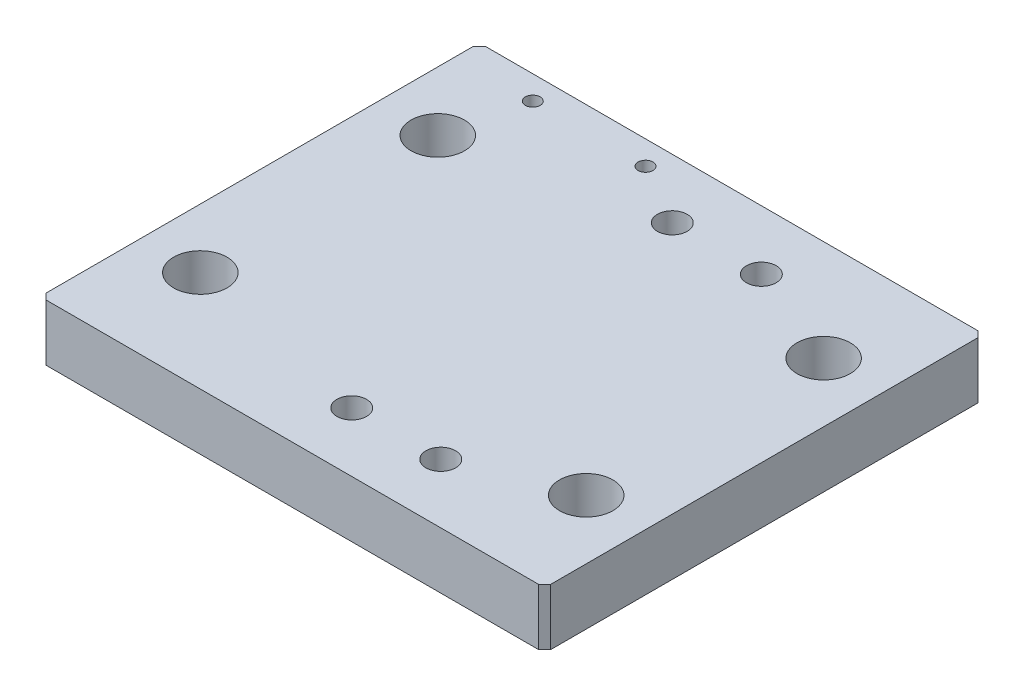
SolidWorks part; units mm, degrees
ref_plane "Front Plane" through (0, 0, 0) normal (0, 0, 1) x (1, 0, 0)
ref_plane "Top Plane" through (0, 0, 0) normal (0, 1, 0) x (1, 0, 0)
ref_plane "Right Plane" through (0, 0, 0) normal (1, 0, 0) x (0, 0, -1)
sketch "Sketch1" plane through (0, 0, 0) normal (0, 1, 0) x (1, 0, 0)
  line L0 (-29.5, 33) -> (-10.5, 33) construction
  line L1 (-42.5, 37) -> (42.5, 37)
  line L2 (-42.5, 37) -> (-42.5, -37)
  line L3 (-42.5, -37) -> (42.5, -37)
  line L4 (42.5, 37) -> (42.5, -37)
  line L5 (-42.5, 37) -> (42.5, -37) construction
  line L6 (-42.5, -37) -> (42.5, 37) construction
  line L7 (32.5, 20) -> (-32.5, 20) construction
  line L8 (32.5, 20) -> (32.5, -20) construction
  line L9 (32.5, -20) -> (-32.5, -20) construction
  line L10 (-32.5, 20) -> (-32.5, -20) construction
  line L11 (32.5, 20) -> (-32.5, -20) construction
  line L12 (32.5, -20) -> (-32.5, 20) construction
  line L13 (0, 27) -> (15, 27) construction
  line L14 (0, 27) -> (0, -27) construction
  line L15 (0, -27) -> (15, -27) construction
  line L16 (15, 27) -> (15, -27) construction
  point P0 (0, 0)
  point P6 (0, 0)
  point P17 (-20, 33)
  dimension "D1" = 15
  dimension "D2" = 54
  dimension "D3" = 65
  dimension "D4" = 40
  dimension "D5" = 10
  dimension "D6" = 10
  dimension "D7" = 19
  dimension "D8" = 20
  dimension "D9" = 33
extrude "Boss-Extrude1" add sketch "Sketch1" along normal blind 9.525
hole_wizard "M8 Clearance Hole1" positions "Sketch2" profile "Sketch3" hole size "M8" standard "ANSI Metric" end condition through all
sketch "Sketch2" plane through (0, 9.525, 0) normal (0, 1, 0) x (1, 0, 0)
  point P0 (-32.5, 20)
  point P3 (32.5, 20)
  point P6 (32.5, -20)
  point P9 (-32.5, -20)
sketch "Sketch3" plane through (-32.5, 9.525, -20) normal (1, 0, 0) x (0, 0, 1)
  line L0 (0, 0) -> (0, 9.525)
  line L1 (0, 9.525) -> (4.5, 9.525)
  line L2 (4.5, 9.525) -> (4.5, 0)
  line L5 (4.5, 0) -> (0, 0)
  line L11 (0, -6.35) -> (0, 107.95) construction
  dimension "Thru Hole Dia." = 9
  dimension "Thru Hole Depth" = 9.525
hole_wizard "M6x1.0 Tapped Hole1" positions "Sketch4" profile "Sketch5" tap size "M6x1.0" standard "ANSI Metric" end condition up to next
sketch "Sketch4" plane through (0, 9.525, 0) normal (0, 1, 0) x (1, 0, 0)
  point P0 (0, 27)
  point P3 (15, 27)
  point P6 (15, -27)
  point P9 (0, -27)
sketch "Sketch5" plane through (0, 9.525, -27) normal (1, 0, 0) x (0, 0, 1)
  line L0 (0, 0) -> (0, 9.525)
  line L1 (0, 9.525) -> (2.5, 9.525)
  line L2 (2.5, 9.525) -> (2.5, 0)
  line L5 (2.5, 0) -> (0, 0)
  line L11 (0, -6.35) -> (0, 107.95) construction
  dimension "Thru Tap Drill Dia." = 5
  dimension "Thru Tap Drill Depth" = 9.525
cosmetic thread "Hole Thread1" parameters "D2"=6
cosmetic thread "Hole Thread2" parameters "D2"=6
cosmetic thread "Hole Thread3" parameters "D2"=6
cosmetic thread "Hole Thread4" parameters "D2"=6
hole_wizard "M6x1.0 Tapped Hole2" [suppressed] positions "Sketch8" profile "Sketch9" tap size "M6x1.0" standard "ANSI Metric"
sketch "Sketch8" plane through (0, 9.525, 0) normal (0, 1, 0) x (1, 0, 0)
  point P0 (0, 27)
  point P3 (0, -27)
sketch "Sketch9" plane through (0, 9.525, -27) normal (1, 0, 0) x (0, 0, 1)
  line L0 (0, 0) -> (0, 9.525)
  line L1 (0, 9.525) -> (2.5, 9.525)
  line L2 (2.5, 9.525) -> (2.5, 0)
  line L5 (2.5, 0) -> (0, 0)
  line L11 (0, -6.35) -> (0, 107.95) construction
  dimension "Thru Tap Drill Dia." = 5
  dimension "Thru Tap Drill Depth" = 9.525
cosmetic thread "Hole Thread7" [suppressed] parameters "D2"=6
cosmetic thread "Hole Thread8" [suppressed] parameters "D2"=6
hole_wizard "M3x0.5 Tapped Hole1" positions "Sketch6" profile "Sketch7" tap size "M3x0.5" standard "ANSI Metric" end condition up to next
sketch "Sketch6" plane through (0, 9.525, 0) normal (0, 1, 0) x (1, 0, 0)
  point P0 (-29.5, 33)
  point P3 (-10.5, 33)
sketch "Sketch7" plane through (-29.5, 9.525, -33) normal (1, 0, 0) x (0, 0, 1)
  line L0 (0, 0) -> (0, 9.525)
  line L1 (0, 9.525) -> (1.25, 9.525)
  line L2 (1.25, 9.525) -> (1.25, 0)
  line L5 (1.25, 0) -> (0, 0)
  line L11 (0, -6.35) -> (0, 107.95) construction
  dimension "Thru Tap Drill Dia." = 2.5
  dimension "Thru Tap Drill Depth" = 9.525
cosmetic thread "Hole Thread5" parameters "D2"=3
cosmetic thread "Hole Thread6" parameters "D2"=3
chamfer "Chamfer1" distance 1 angle 45 4 edges at (42.5, 4.7625, 37) (-42.5, 4.7625, 37) (42.5, 4.7625, -37) (-42.5, 4.7625, -37)
